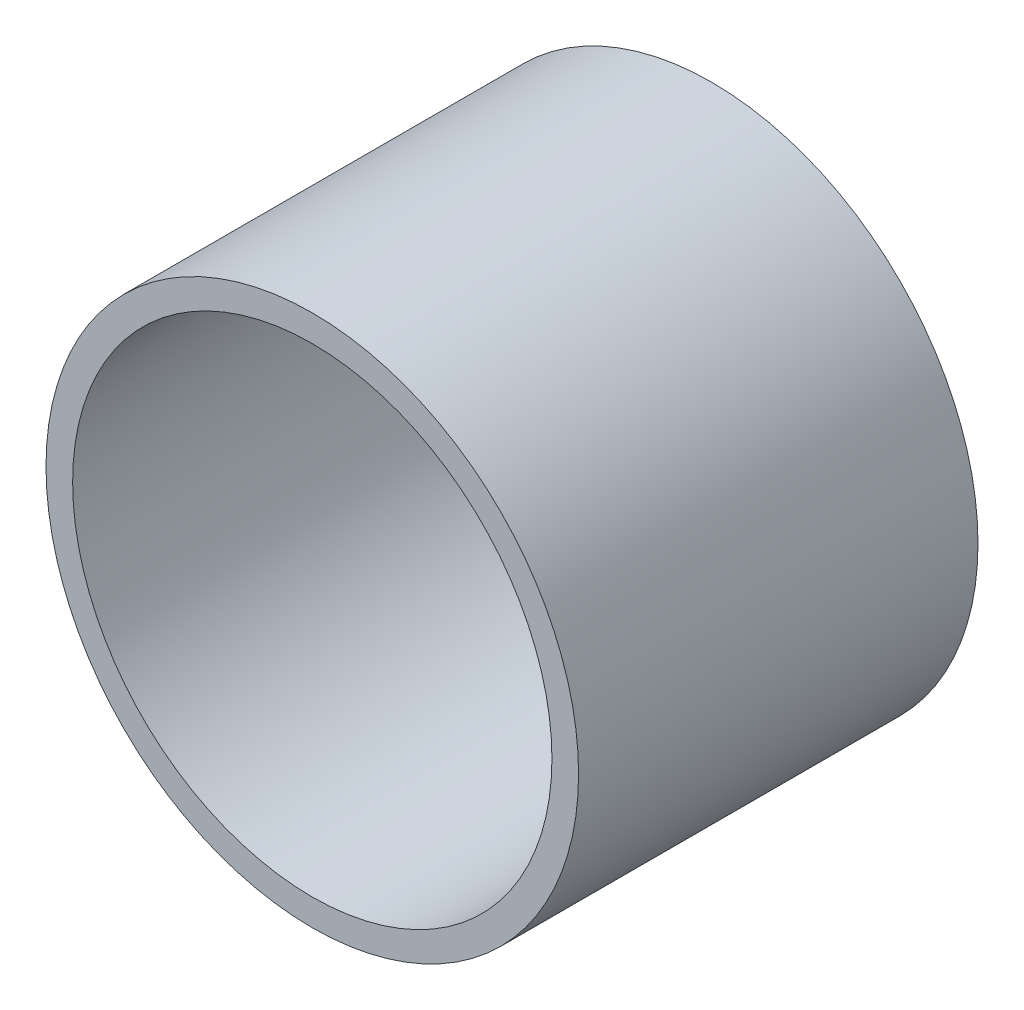
SolidWorks part; units mm, degrees
ref_plane "Front" through (0, 0, 0) normal (0, 0, 1) x (1, 0, 0)
ref_plane "Top" through (0, 0, 0) normal (0, 1, 0) x (1, 0, 0)
ref_plane "Right" through (0, 0, 0) normal (1, 0, 0) x (0, 0, -1)
sketch "Эскиз1" plane through (0, 0, 0) normal (0, 0, 1) x (1, 0, 0)
  circle A0 centre (0, 0) radius 20
  dimension "D1" = 40
extrude "Бобышка-Вытянуть1" add sketch "Эскиз1" along normal blind 30
sketch "Эскиз2" plane through (0, 0, 30) normal (0, 0, 1) x (1, 0, 0)
  circle A0 centre (0, 0) radius 18
  dimension "D1" = 36
extrude "Вырез-Вытянуть1" cut sketch "Эскиз2" against normal through all
